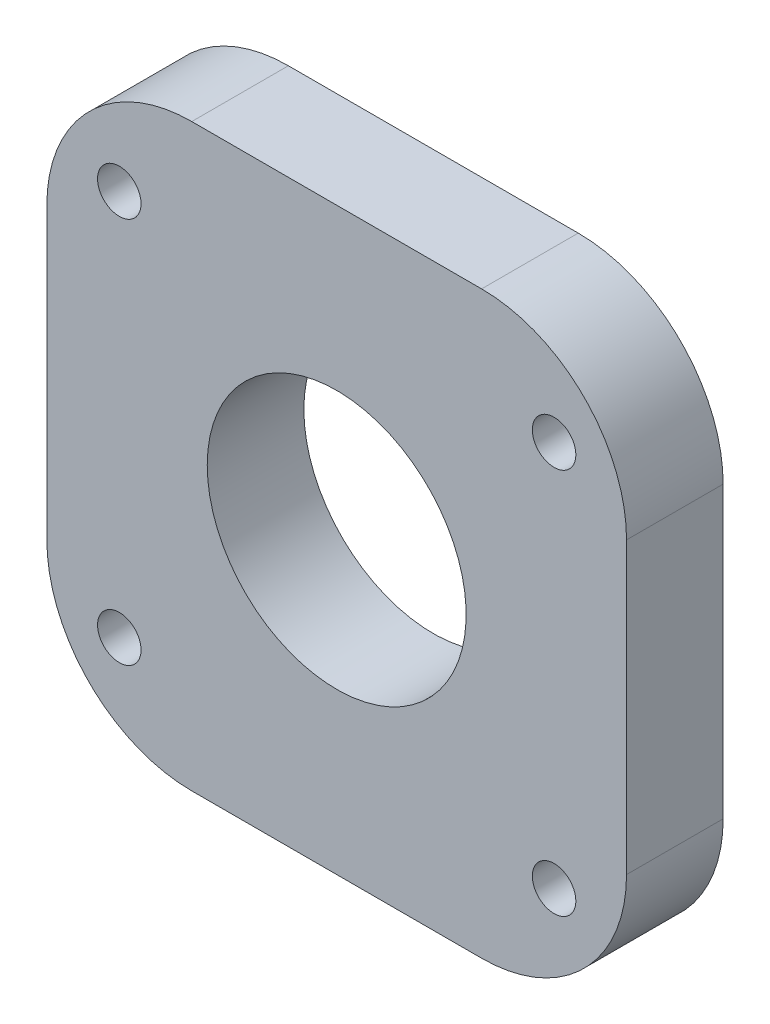
SolidWorks part; units mm, degrees
ref_plane "Plan de face" through (0, 0, 0) normal (0, 0, 1) x (1, 0, 0)
ref_plane "Plan de dessus" through (0, 0, 0) normal (0, 1, 0) x (1, 0, 0)
ref_plane "Plan de droite" through (0, 0, 0) normal (1, 0, 0) x (0, 0, -1)
ref_plane "Plan1" through (0, 0, 0) normal (0, 0, -1) x (-1, 0, 0)
sketch "Esquisse1" plane through (0, 0, 0) normal (0, 0, -1) x (-1, 0, 0)
  line L1 (30, -30) -> (-30, -30)
  line L2 (30, -30) -> (30, 30)
  line L3 (30, 30) -> (-30, 30)
  line L4 (-30, -30) -> (-30, 30)
  line L5 (30, -30) -> (-30, 30) construction
  line L6 (30, 30) -> (-30, -30) construction
  point P0 (0, 0)
  dimension "D1" = 60
  dimension "D2" = 60
extrude "Boss.-Extru.1" add sketch "Esquisse1" against normal blind 10
hole_wizard "Diamètre du perçage Ø4.5 (4.5)1" positions "Esquisse3" profile "Esquisse2" hole size "Ø4.5" standard "Ansi Metric" end condition through all
sketch "Esquisse3" plane through (0, 0, 0) normal (0, 0, -1) x (-1, 0, 0)
  line L7 (22.5, -20) -> (-22.5, -20) construction
  line L8 (22.5, -20) -> (22.5, 20) construction
  line L9 (22.5, 20) -> (-22.5, 20) construction
  line L10 (-22.5, -20) -> (-22.5, 20) construction
  line L11 (22.5, -20) -> (-22.5, 20) construction
  line L12 (22.5, 20) -> (-22.5, -20) construction
  point P77 (22.5, 20)
  point P80 (-22.5, 20)
  point P83 (-22.5, -20)
  point P86 (22.5, -20)
  dimension "D1" = 45
  dimension "D2" = 40
sketch "Esquisse2" plane through (-22.5, 20, 0) normal (1, 0, 0) x (0, 1, 0)
  line L0 (0, 0) -> (0, 10)
  line L1 (0, 10) -> (2.25, 10)
  line L2 (2.25, 10) -> (2.25, 0)
  line L5 (2.25, 0) -> (0, 0)
  line L11 (0, -6.35) -> (0, 107.95) construction
  dimension "Diamètre du perçage jusqu'au prochain" = 4.5
  dimension "Profondeur du perçage jusqu'au prochain" = 10
hole_wizard "Diamètre du perçage Ø5.1 (5.1)1" positions "Esquisse5" profile "Esquisse4" hole size "Ø5.1" standard "Ansi Metric"
sketch "Esquisse5" plane through (0, 0, 0) normal (0, 0, -1) x (-1, 0, 0)
  line L3 (0, 17.95) -> (0, -17.95) construction
  line L5 (-13.4, 0) -> (-22.5, 0) construction
  circle A0 centre (0, 0) radius 13.4 construction
  circle A1 centre (0, 0) radius 22.5 construction
  circle A2 centre (0, 0) radius 17.95 construction
  point P15 (-14.0339, 11.1916)
  point P24 (-7.7882, 16.1724)
  point P25 (0, 17.95)
  point P26 (7.7882, 16.1724)
  point P27 (14.0339, 11.1916)
  point P28 (17.5, 3.9943)
  point P29 (17.5, -3.9943)
  point P30 (14.0339, -11.1916)
  point P31 (7.7882, -16.1724)
  point P32 (0, -17.95)
  point P33 (-7.7882, -16.1724)
  point P34 (-14.0339, -11.1916)
  point P35 (-17.5, -3.9943)
  point P36 (-17.5, 3.9943)
  point P60 (-17.95, 0)
  dimension "D3" = 26.8
  dimension "D4" = 45
  dimension "D5" = 35.9
  dimension "D2" = 14
sketch "Esquisse4" plane through (14.0339, 11.1916, 0) normal (1, 0, 0) x (0, 1, 0)
  line L0 (0, 0) -> (0, 8.5322)
  line L1 (0, 8.5322) -> (2.55, 7)
  line L2 (2.55, 7) -> (2.55, 0)
  line L5 (2.55, 0) -> (0, 0)
  line L10 (0, 8.5322) -> (-2.55, 7) construction
  line L11 (0, -6.35) -> (0, 107.95) construction
  dimension "Diamètre du perçage" = 5.1
  dimension "Profondeur du perçage" = 7
  dimension "Angle de pointe" = 118
sketch "Esquisse9" plane through (0, 0, 0) normal (0, 0, -1) x (-1, 0, 0)
  circle A0 centre (0, 0) radius 13.4
  dimension "D1" = 26.8
extrude "Enlèv. mat.-Extru.2" cut sketch "Esquisse9" against normal through all
fillet "Congé3" radius 15 4 edges at (30, -30, 5) (-30, -30, 5) (-30, 30, 5) (30, 30, 5)
